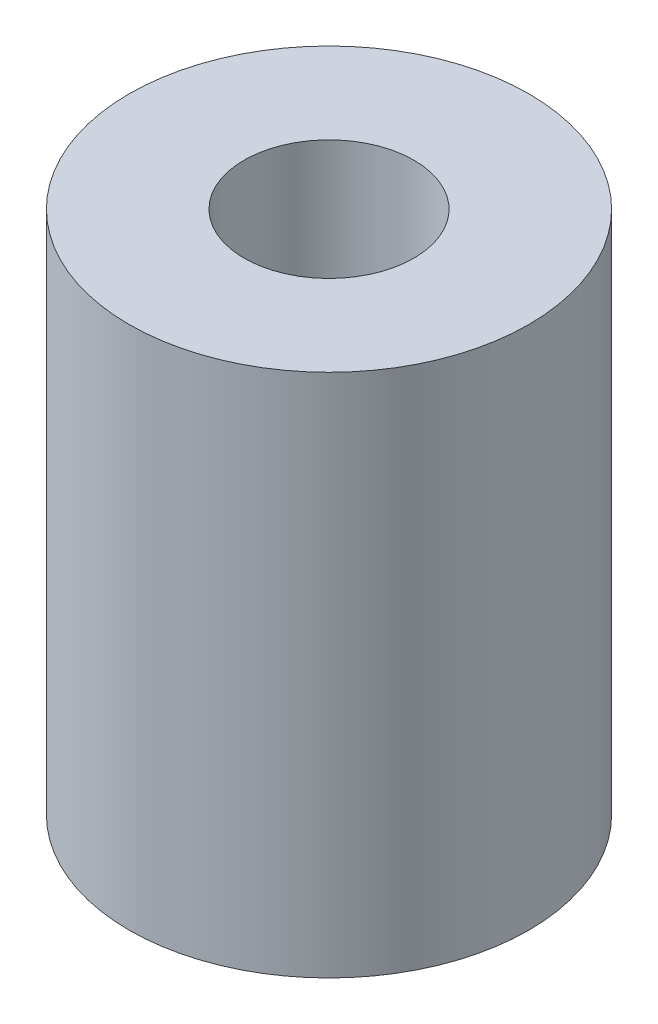
SolidWorks part; units mm, degrees
material "Сплав 2024"
ref_plane "Спереди" through (0, 0, 0) normal (0, 0, 1) x (1, 0, 0)
ref_plane "Сверху" through (0, 0, 0) normal (0, 1, 0) x (1, 0, 0)
ref_plane "Справа" through (0, 0, 0) normal (1, 0, 0) x (0, 0, -1)
sketch "Эскиз1" plane through (0, 0, 0) normal (0, 1, 0) x (1, 0, 0)
  circle A0 centre (0, 0) radius 4
  dimension "D1" = 8
extrude "Бобышка-Вытянуть1" add sketch "Эскиз1" along normal blind 10.5
hole_wizard "Отверстие с зазором M31" positions "Эскиз3" profile "Эскиз2" hole size "M3" standard "Ansi Metric" end condition through all
sketch "Эскиз3" plane through (0, 0, 0) normal (0, -1, 0) x (-1, 0, 0)
  point P0 (0, 0)
sketch "Эскиз2" plane through (0, 0, 0) normal (1, 0, 0) x (0, 0, -1)
  line L0 (0, 0) -> (0, 10.5)
  line L1 (0, 10.5) -> (1.7, 10.5)
  line L2 (1.7, 10.5) -> (1.7, 0)
  line L5 (1.7, 0) -> (0, 0)
  line L11 (0, -6.35) -> (0, 107.95) construction
  dimension "Диаметр сквозного отверстия" = 3.4
  dimension "Глубина сквозного отверстия" = 10.5
hole_wizard "Отверстие обработанное метчиком M4x0.72" positions "Эскиз5" profile "Эскиз4" tap size "M4x0.7" standard "Ansi Metric"
sketch "Эскиз5" plane through (0, 30, 0) normal (0, 1, 0) x (1, 0, 0)
  point P0 (0, 0)
sketch "Эскиз4" plane through (0, 30, 0) normal (1, 0, 0) x (0, 0, 1)
  line L0 (0, 0) -> (0, 12.4914)
  line L1 (0, 12.4914) -> (1.65, 11.5)
  line L2 (1.65, 11.5) -> (1.65, 0)
  line L5 (1.65, 0) -> (0, 0)
  line L10 (0, 12.4914) -> (-1.65, 11.5) construction
  line L11 (0, -6.35) -> (0, 107.95) construction
  dimension "Диаметр сверла" = 3.3
  dimension "Глубина сверла" = 11.5
  dimension "Угол заточки сверла" = 118
